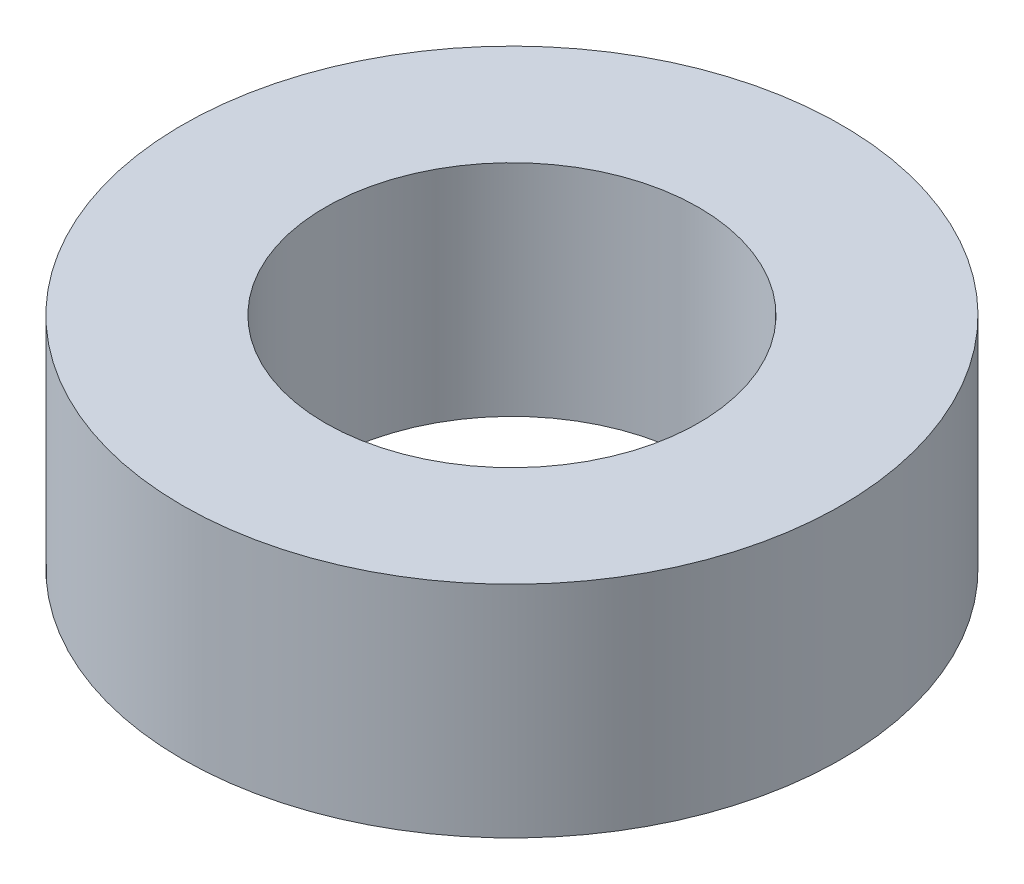
SolidWorks part; units mm, degrees
material "6061-T6 (SS)"
ref_plane "前视基准面" through (0, 0, 0) normal (0, 0, 1) x (1, 0, 0)
ref_plane "上视基准面" through (0, 0, 0) normal (0, 1, 0) x (1, 0, 0)
ref_plane "右视基准面" through (0, 0, 0) normal (1, 0, 0) x (0, 0, -1)
sketch "草图1" plane through (0, 0, 0) normal (0, 1, 0) x (1, 0, 0)
  circle A0 centre (0, 0) radius 1.7
  circle A1 centre (0, 0) radius 3
  dimension "D1" = 3.4
  dimension "D2" = 6
extrude "凸台-拉伸1" add sketch "草图1" along normal blind 2
